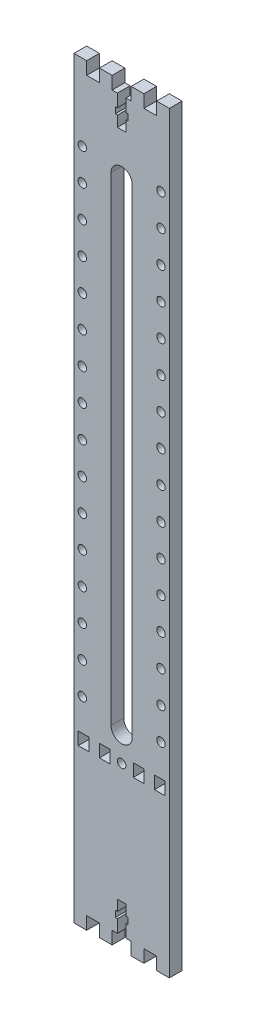
SolidWorks part; units mm, degrees
material "Balsa"
ref_plane "Plan de face" through (0, 0, 0) normal (0, 0, 1) x (1, 0, 0)
ref_plane "Plan de dessus" through (0, 0, 0) normal (0, 1, 0) x (1, 0, 0)
ref_plane "Plan de droite" through (0, 0, 0) normal (1, 0, 0) x (0, 0, -1)
sketch "Esquisse1" plane through (0, 0, 0) normal (0, 0, 1) x (1, 0, 0)
  line L0 (-5.5, 70.5) -> (5.5, 70.5) construction
  line L1 (-22.5, 343.5) -> (22.5, 343.5)
  line L2 (-22.5, 343.5) -> (-22.5, 0)
  line L3 (-22.5, 0) -> (22.5, 0)
  line L4 (22.5, 343.5) -> (22.5, 0)
  line L13 (-22.5, 138.5) -> (22.5, 138.5) construction
  line L22 (-22.5, 67.5) -> (22.5, 67.5) construction
  line L24 (-20.5, 67.5) -> (-15.5, 67.5)
  line L25 (-20.5, 67.5) -> (-20.5, 73.5)
  line L26 (-20.5, 73.5) -> (-15.5, 73.5)
  line L27 (-15.5, 67.5) -> (-15.5, 73.5)
  line L28 (-10.5, 67.5) -> (-5.5, 67.5)
  line L29 (-10.5, 67.5) -> (-10.5, 73.5)
  line L30 (-10.5, 73.5) -> (-5.5, 73.5)
  line L31 (-5.5, 67.5) -> (-5.5, 73.5)
  line L32 (10.5, 67.5) -> (5.5, 67.5)
  line L33 (10.5, 67.5) -> (10.5, 73.5)
  line L34 (10.5, 73.5) -> (5.5, 73.5)
  line L35 (5.5, 67.5) -> (5.5, 73.5)
  line L36 (20.5, 67.5) -> (15.5, 67.5)
  line L37 (20.5, 67.5) -> (20.5, 73.5)
  line L38 (20.5, 73.5) -> (15.5, 73.5)
  line L39 (15.5, 67.5) -> (15.5, 73.5)
  circle A0 centre (0, 70.5) radius 2
  dimension "D4" = 4
  dimension "D1" = 45
  dimension "D2" = 343.5
  dimension "D3" = 2
  dimension "D7" = 205
  dimension "D8" = 67.5
  dimension "D9" = 5
  dimension "D10" = 5
  dimension "D11" = 5
  dimension "D12" = 5
  dimension "D13" = 5
  dimension "D14" = 5
  dimension "D15" = 2
  dimension "D16" = 6
extrude "Boss.-Extru.1" add sketch "Esquisse1" along normal blind 6
sketch "Esquisse2" plane through (0, 343.5, 0) normal (0, 1, 0) x (1, 0, 0)
  line L0 (22.5, -6) -> (-22.5, -6) construction
  line L1 (-22.5, 0) -> (-16.5, 0)
  line L2 (-22.5, 0) -> (-22.5, -6)
  line L3 (-22.5, -6) -> (-16.5, -6)
  line L4 (-16.5, 0) -> (-16.5, -6)
  line L5 (22.5, 0) -> (-22.5, 0) construction
  line L6 (22.5, 0) -> (16.5, 0)
  line L7 (22.5, 0) -> (22.5, -6)
  line L8 (22.5, -6) -> (16.5, -6)
  line L9 (16.5, 0) -> (16.5, -6)
  line L10 (10.5, 0) -> (4.5, 0)
  line L11 (10.5, 0) -> (10.5, -6)
  line L12 (10.5, -6) -> (4.5, -6)
  line L13 (4.5, 0) -> (4.5, -6)
  line L15 (-10.5, 0) -> (-4.5, 0)
  line L16 (-10.5, 0) -> (-10.5, -6)
  line L17 (-10.5, -6) -> (-4.5, -6)
  line L18 (-4.5, 0) -> (-4.5, -6)
  dimension "D1" = 6
  dimension "D2" = 6
  dimension "D3" = 6
  dimension "D4" = 6
  dimension "D5" = 6
  dimension "D6" = 6
extrude "Boss.-Extru.2" add sketch "Esquisse2" along normal blind 6
sketch "Esquisse3" plane through (0, 0, 6) normal (0, 0, 1) x (1, 0, 0)
  line L0 (4.5, 343.5) -> (-4.5, 343.5) construction
  line L1 (-2, 343.5) -> (2, 343.5)
  line L2 (-2, 343.5) -> (-2, 337.5)
  line L3 (-2, 329.5) -> (2, 329.5)
  line L4 (2, 343.5) -> (2, 337.5)
  line L5 (0, 343.5) -> (0, 258.7814) construction
  line L6 (-3, 337.5) -> (-2, 337.5)
  line L7 (-3, 337.5) -> (-3, 334.5)
  line L8 (-3, 334.5) -> (-2, 334.5)
  line L9 (3, 337.5) -> (3, 334.5)
  line L10 (-2, 334.5) -> (-2, 329.5)
  line L11 (2, 337.5) -> (3, 337.5)
  line L12 (2, 334.5) -> (3, 334.5)
  line L13 (2, 334.5) -> (2, 329.5)
  dimension "D1" = 4
  dimension "D2" = 14
  dimension "D3" = 3
  dimension "D4" = 6
  dimension "D5" = 1
extrude "Enlèv. mat.-Extru.1" cut sketch "Esquisse3" against normal through all
ref_plane "Plan1" through (0, 171.75, 0) normal (0, 1, 0) x (1, 0, 0)
mirror "Symétrie1" about plane through (0, 171.75, 0) normal (0, 1, 0) of "Enlèv. mat.-Extru.1", "Boss.-Extru.2"
sketch "Esquisse4" plane through (0, 0, 6) normal (0, 0, 1) x (1, 0, 0)
  line L0 (-22.5, 88.5) -> (22.5, 88.5) construction
  line L1 (-22.5, 349.5) -> (-22.5, -6) construction
  line L2 (22.5, -6) -> (22.5, 349.5) construction
  line L3 (-5.5, 73.5) -> (-10.5, 73.5) construction
  line L4 (0, 88.5) -> (0, 322.9833) construction
  line L5 (0, 83.5) -> (0, 309.5) construction
  line L6 (-5, 83.5) -> (-5, 309.5)
  line L7 (5, 83.5) -> (5, 309.5)
  line L8 (-2, 329.5) -> (2, 329.5) construction
  circle A0 centre (-18.575, 88.5) radius 2
  circle A1 centre (18.575, 88.5) radius 2
  circle A2 centre (-18.575, 103.5) radius 2
  circle A3 centre (18.575, 103.5) radius 2
  circle A4 centre (-18.575, 118.5) radius 2
  circle A5 centre (18.575, 118.5) radius 2
  circle A6 centre (-18.575, 133.5) radius 2
  circle A7 centre (18.575, 133.5) radius 2
  circle A8 centre (-18.575, 148.5) radius 2
  circle A9 centre (18.575, 148.5) radius 2
  circle A10 centre (-18.575, 163.5) radius 2
  circle A11 centre (18.575, 163.5) radius 2
  circle A12 centre (-18.575, 178.5) radius 2
  circle A13 centre (18.575, 178.5) radius 2
  circle A14 centre (-18.575, 193.5) radius 2
  circle A15 centre (18.575, 193.5) radius 2
  circle A16 centre (-18.575, 208.5) radius 2
  circle A17 centre (18.575, 208.5) radius 2
  circle A18 centre (-18.575, 223.5) radius 2
  circle A19 centre (18.575, 223.5) radius 2
  circle A20 centre (-18.575, 238.5) radius 2
  circle A21 centre (18.575, 238.5) radius 2
  circle A22 centre (-18.575, 253.5) radius 2
  circle A23 centre (18.575, 253.5) radius 2
  circle A24 centre (-18.575, 268.5) radius 2
  circle A25 centre (18.575, 268.5) radius 2
  circle A26 centre (-18.575, 283.5) radius 2
  circle A27 centre (18.575, 283.5) radius 2
  circle A28 centre (-18.575, 298.5) radius 2
  circle A29 centre (18.575, 298.5) radius 2
  circle A30 centre (-18.575, 313.5) radius 2
  circle A31 centre (18.575, 313.5) radius 2
  arc A32 (-5, 83.5) -> (5, 83.5) centre (0, 83.5) ccw
  arc A33 (5, 309.5) -> (-5, 309.5) centre (0, 309.5) ccw
  point P76 (0, 196.5)
  point P81 (0, 329.5)
  dimension "D1" = 4
  dimension "D2" = 37.15
  dimension "D3" = 4
  dimension "D4" = 15
  dimension "D5" = 16
  dimension "D6" = 10
  dimension "D7" = 5
  dimension "D8" = 20
extrude "Enlèv. mat.-Extru.2" cut sketch "Esquisse4" against normal blind 6
